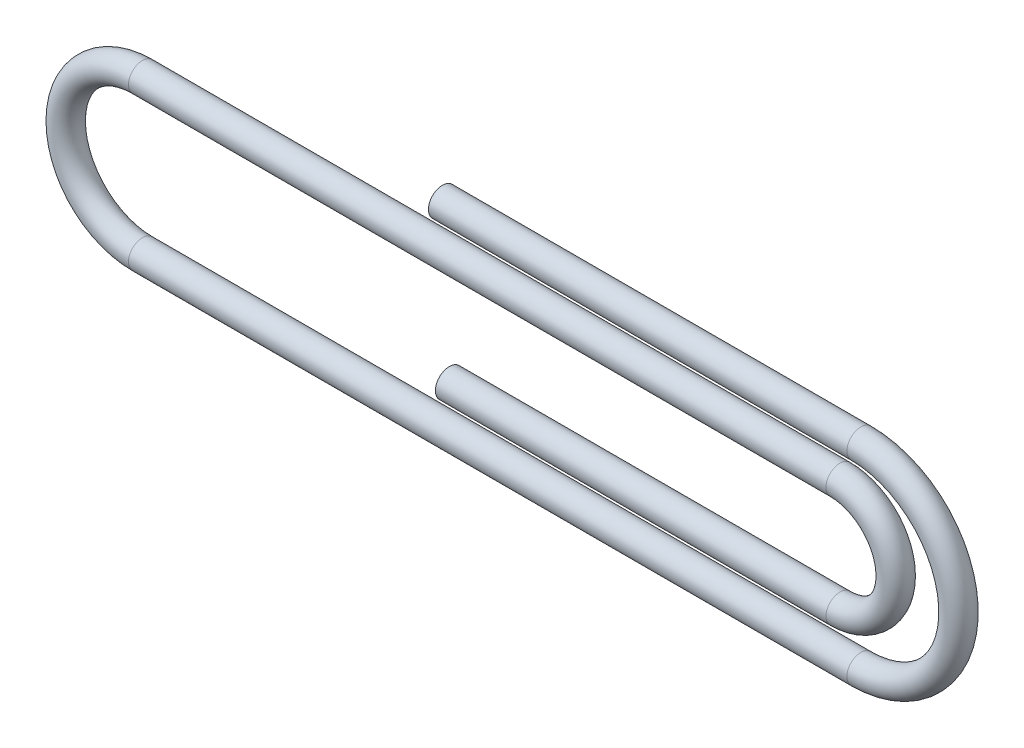
SolidWorks part; units mm, degrees
ref_plane "Front Plane" through (0, 0, 0) normal (0, 0, 1) x (1, 0, 0)
ref_plane "Top Plane" through (0, 0, 0) normal (0, 1, 0) x (1, 0, 0)
ref_plane "Right Plane" through (0, 0, 0) normal (1, 0, 0) x (0, 0, -1)
sketch "Sketch1" plane through (0, 0, 0) normal (0, 0, 1) x (1, 0, 0)
  line L0 (0, 0) -> (15, 0)
  line L1 (14.25, -5.5) -> (0.25, -5.5)
  line L2 (15, -7) -> (-10.75, -7)
  line L3 (-10.75, -1.5) -> (14.25, -1.5)
  arc A0 (15, -7) -> (15, 0) centre (15, -3.5) ccw
  arc A1 (-10.75, -1.5) -> (-10.75, -7) centre (-10.75, -4.25) ccw
  arc A2 (14.25, -5.5) -> (14.25, -1.5) centre (14.25, -3.5) ccw
  point P3 (-13.5, -4.25)
  point P9 (18.5, -3.5)
  dimension "D1" = 7
  dimension "D2" = 32
  dimension "D5" = 1.5
  dimension "D3" = 15
  dimension "D4" = 25
  dimension "D6" = 1.5
sketch "Sketch2" plane through (0, 0, 0) normal (1, 0, 0) x (0, 0, -1)
  circle A0 centre (0, 0) radius 0.5
sweep "Sweep1" add profiles "Sketch2" path "Sketch1"
